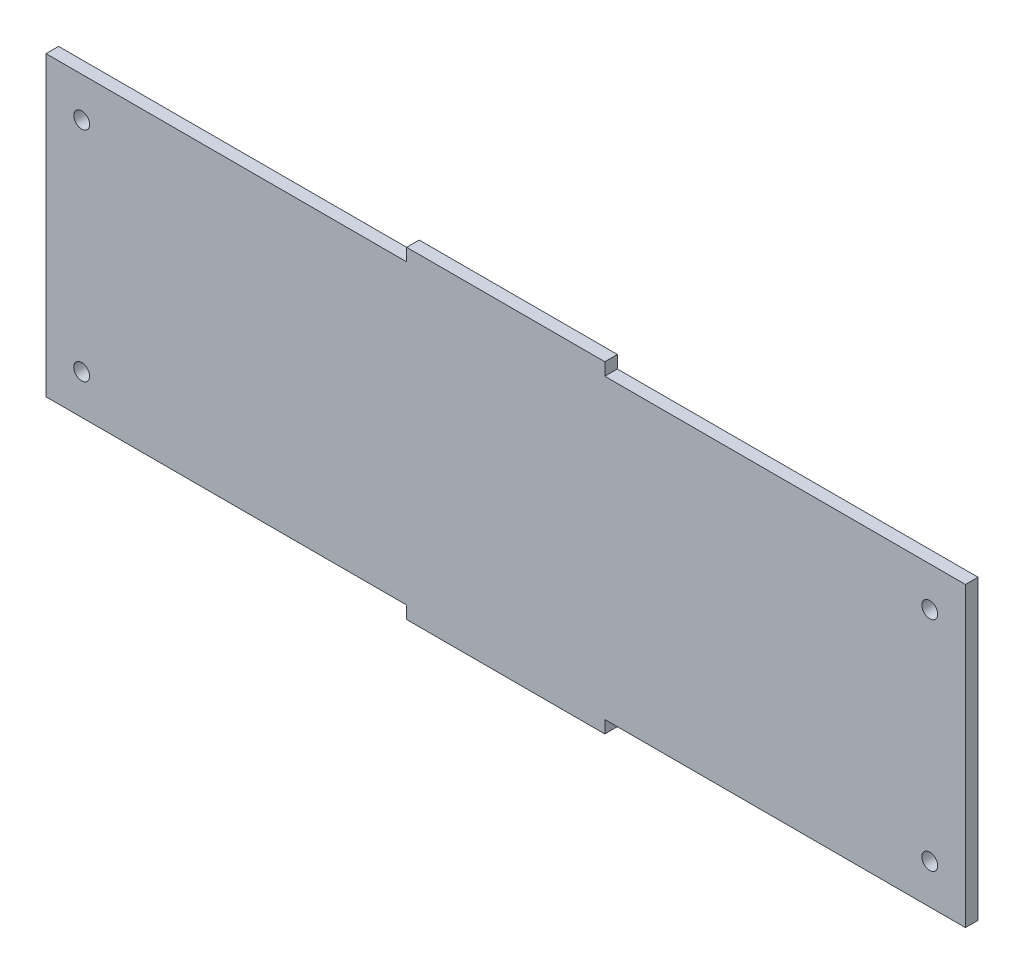
SolidWorks part; units mm, degrees
ref_plane "Front Plane" through (0, 0, 0) normal (0, 0, 1) x (1, 0, 0)
ref_plane "Top Plane" through (0, 0, 0) normal (0, 1, 0) x (1, 0, 0)
ref_plane "Right Plane" through (0, 0, 0) normal (1, 0, 0) x (0, 0, -1)
sketch "Sketch1" plane through (0, 0, 0) normal (0, 0, 1) x (1, 0, 0)
  line L0 (116, 75) -> (116, 0) construction
  line L1 (0, 0) -> (232, 0)
  line L2 (0, 0) -> (0, 75)
  line L3 (0, 75) -> (232, 75)
  line L4 (232, 0) -> (232, 75)
  line L5 (0, 37.5) -> (232, 37.5) construction
  circle A0 centre (9, 65) radius 2
  circle A2 centre (9, 10) radius 2
  circle A3 centre (223, 10) radius 2
  circle A4 centre (223, 65) radius 2
  dimension "D3" = 4
  dimension "D1" = 10
  dimension "D2" = 9
  dimension "D4" = 232
  dimension "D5" = 75
extrude "Boss-Extrude1" add sketch "Sketch1" along normal blind 3.175
sketch "Sketch2" plane through (0, 0, 3.175) normal (0, 0, 1) x (1, 0, 0)
  line L0 (0, 0) -> (232, 0) construction
  line L1 (91, 0) -> (141, 0)
  line L2 (91, 0) -> (91, -3.175)
  line L3 (91, -3.175) -> (141, -3.175)
  line L4 (141, 0) -> (141, -3.175)
  line L5 (232, 75) -> (0, 75) construction
  line L6 (91, 75) -> (141, 75)
  line L7 (91, 75) -> (91, 78.175)
  line L8 (91, 78.175) -> (141, 78.175)
  line L9 (141, 75) -> (141, 78.175)
  line L10 (116, -3.175) -> (116, 78.175) construction
  point P14 (116, 0)
  dimension "D1" = 50
  dimension "D2" = 3.175
extrude "Boss-Extrude2" add sketch "Sketch2" against normal up to surface (3.175 mm away) up to face at (225, 10, 0)
